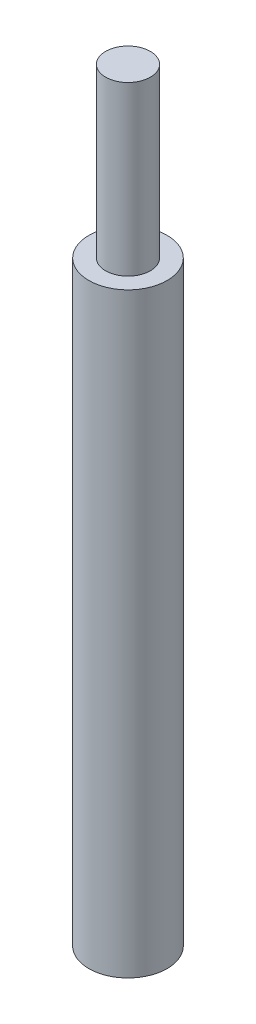
SolidWorks part; units mm, degrees
ref_plane "Front Plane" through (0, 0, 0) normal (0, 0, 1) x (1, 0, 0)
ref_plane "Top Plane" through (0, 0, 0) normal (0, 1, 0) x (1, 0, 0)
ref_plane "Right Plane" through (0, 0, 0) normal (1, 0, 0) x (0, 0, -1)
sketch "Sketch1" plane through (0, 0, 0) normal (0, 1, 0) x (1, 0, 0)
  circle A0 centre (0, 0) radius 3.5
  dimension "D1" = 7
extrude "Boss-Extrude1" add sketch "Sketch1" along normal blind 53.3
sketch "Sketch3" plane through (0, 53.3, 0) normal (0, 1, 0) x (1, 0, 0)
  circle A0 centre (0, 0) radius 2
  dimension "D1" = 4
extrude "Boss-Extrude2" add sketch "Sketch3" along normal blind 15
